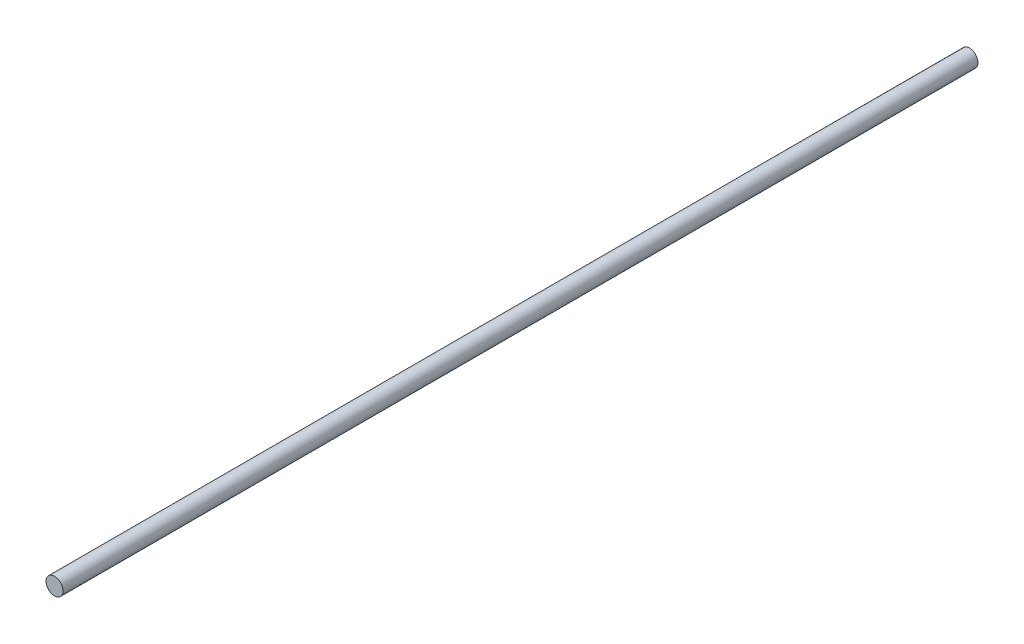
SolidWorks part; units mm, degrees
ref_plane "前基準面" through (0, 0, 0) normal (0, 0, 1) x (1, 0, 0)
ref_plane "上基準面" through (0, 0, 0) normal (0, 1, 0) x (1, 0, 0)
ref_plane "右基準面" through (0, 0, 0) normal (1, 0, 0) x (0, 0, -1)
sketch "草圖1" plane through (0, 0, 0) normal (0, 0, 1) x (1, 0, 0)
  circle A0 centre (0, 0) radius 4
  dimension "D1" = 8
extrude "填料-伸長1" add sketch "草圖1" along normal blind 430
